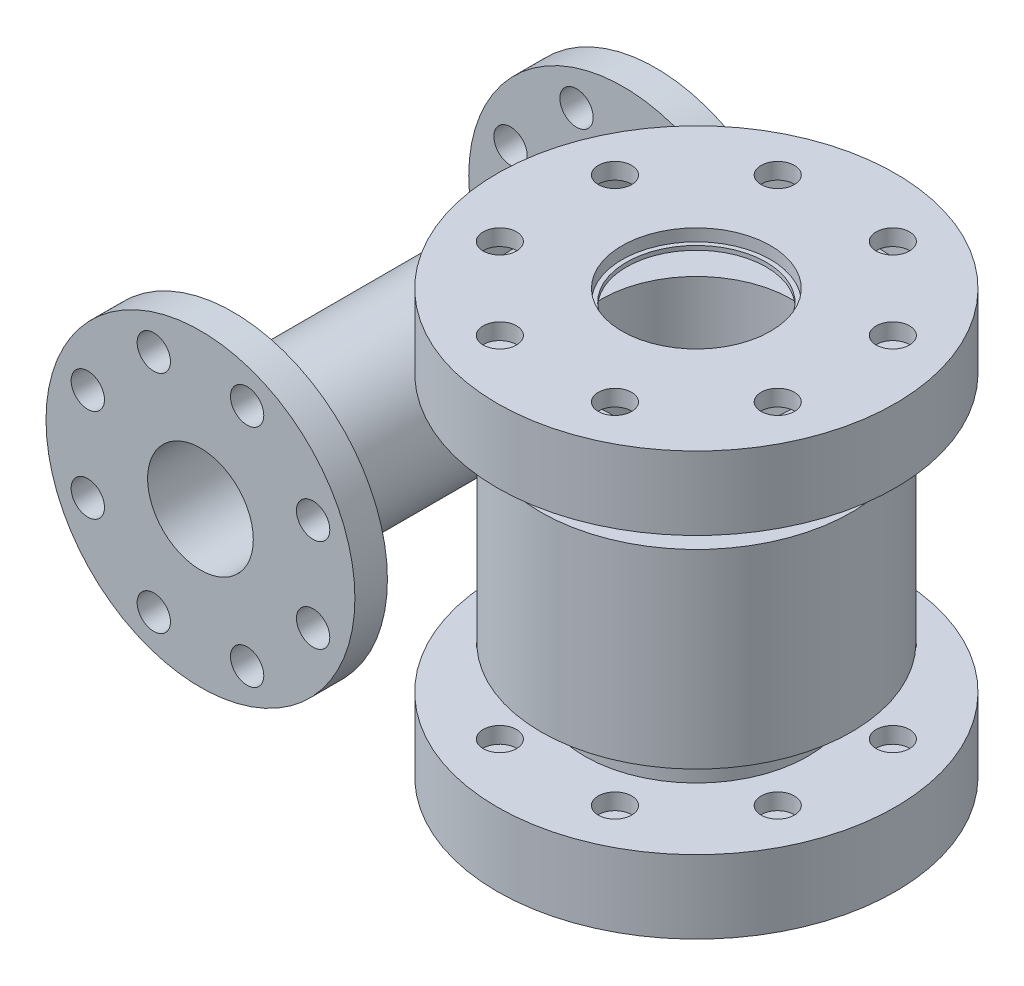
SolidWorks part; units mm, degrees
ref_plane "Front Plane" through (0, 0, 0) normal (0, 0, 1) x (1, 0, 0)
ref_plane "Top Plane" through (0, 0, 0) normal (0, 1, 0) x (1, 0, 0)
ref_plane "Right Plane" through (0, 0, 0) normal (1, 0, 0) x (0, 0, -1)
sketch "Sketch1" plane through (0, 0, 0) normal (0, 0, 1) x (1, 0, 0)
  line L0 (30.2632, 202.5921) -> (112.5, 202.5921)
  line L1 (112.5, 202.5921) -> (112.5, 177.5921)
  line L2 (112.5, 177.5921) -> (58.5526, 177.5921)
  line L3 (58.5526, 177.5921) -> (58.5526, 131.0921)
  line L4 (58.5526, 131.0921) -> (85.5263, 131.0921)
  line L5 (85.5263, 131.0921) -> (85.5263, 34.0921)
  line L6 (85.5263, 34.0921) -> (58.5526, 34.0921)
  line L7 (58.5526, 34.0921) -> (58.5526, -12.4079)
  line L8 (58.5526, -12.4079) -> (112.5, -12.4079)
  line L9 (112.5, -12.4079) -> (112.5, -37.4079)
  line L10 (112.5, -37.4079) -> (37.3712, -37.4079)
  line L11 (0, 217.4342) -> (0, -150.9868) construction
  line L12 (37.3712, -37.4079) -> (0, -37.4079)
  line L13 (30.2632, 202.5921) -> (0, 202.5921)
  point P2 (112.5, -24.9079)
  dimension "D1" = 25
  dimension "D2" = 97
  dimension "D3" = 12.5
  dimension "D4" = 112.5
  dimension "D5" = 46.5
  dimension "D6" = 46.5
revolve "Revolve-Thin1" add sketch "Sketch1" angle 360 about L11 wall 10
sketch "Sketch2" plane through (0, 212.5921, 0) normal (0, 1, 0) x (1, 0, 0)
  line L0 (0, 92.5) -> (0, 0) construction
  line L1 (0, 0) -> (-35.3982, 85.4589) construction
  circle A0 centre (0, 0) radius 92.5 construction
  circle A1 centre (-35.3982, 85.4589) radius 10.25
  circle A2 centre (35.3982, 85.4589) radius 10.25
  circle A3 centre (85.4589, 35.3982) radius 10.25
  circle A4 centre (85.4589, -35.3982) radius 10.25
  circle A5 centre (35.3982, -85.4589) radius 10.25
  circle A6 centre (-35.3982, -85.4589) radius 10.25
  circle A7 centre (-85.4589, -35.3982) radius 10.25
  circle A8 centre (-85.4589, 35.3982) radius 10.25
  point P22 (0, 0)
  dimension "D1" = 185
  dimension "D3" = 20.5
  dimension "D2" = 22.5
  dimension "D4" = 8
extrude "Cut-Extrude2" cut sketch "Sketch2" against normal up to surface (45 mm away) up to face at (0, 167.5921, 122.5)
sketch "Sketch3" plane through (0, -47.4079, 0) normal (0, -1, 0) x (1, 0, 0)
  line L0 (-35.3982, 85.4589) -> (0, 0) construction
  line L1 (0, 0) -> (0, 92.5) construction
  circle A0 centre (0, 0) radius 92.5 construction
  circle A1 centre (-35.3982, 85.4589) radius 10.25
  circle A2 centre (0.0003, 0.0007) radius 92.5 construction
  circle A3 centre (35.3985, 85.4596) radius 10.25
  circle A4 centre (0.001, 0.001) radius 92.5 construction
  circle A5 centre (85.4599, 35.3992) radius 10.25
  circle A6 centre (0.0017, 0.0007) radius 92.5 construction
  circle A7 centre (85.4606, -35.3975) radius 10.25
  circle A8 centre (0.002, 0) radius 92.5 construction
  circle A9 centre (35.4002, -85.4589) radius 10.25
  circle A10 centre (0.0017, -0.0007) radius 92.5 construction
  circle A11 centre (-35.3965, -85.4596) radius 10.25
  circle A12 centre (0.001, -0.001) radius 92.5 construction
  circle A13 centre (-85.4579, -35.3992) radius 10.25
  circle A14 centre (0.0003, -0.0007) radius 92.5 construction
  circle A15 centre (-85.4586, 35.3975) radius 10.25
  point P37 (0.001, 0)
  dimension "D1" = 185
  dimension "D2" = 20.5
  dimension "D3" = 22.5
  dimension "D4" = 8
extrude "Cut-Extrude3" cut sketch "Sketch3" against normal up to surface (45 mm away) up to face at (0, -2.4079, 68.5526)
sketch "Sketch4" plane through (0, 0, 0) normal (0, 0, 1) x (1, 0, 0)
  line L0 (0, -47.4079) -> (0, 212.5921) construction
  line L1 (-122.5, -47.4079) -> (122.5, -47.4079) construction
  line L2 (122.5, 212.5921) -> (-122.5, 212.5921) construction
  line L3 (0, 82.5921) -> (-165, 82.5921) construction
  circle A0 centre (-165, 82.5921) radius 48.5
  dimension "D2" = 97
  dimension "D1" = 165
extrude "Boss-Extrude2" add sketch "Sketch4" along normal mid plane 280 separate body
sketch3d "3DSketch1"
  circle A0 centre (-165, 82.5921, 140) radius 48.5 construction
  circle A1 centre (-165, 82.5921, 140) radius 48.5
  point P2 (-165, 82.5921, 188.5)
  point P4 (-165, 82.5921, 188.5)
  point P5 (0, 0, 0)
sketch "Sketch5" plane through (0, 0, 140) normal (0, 0, 1) x (1, 0, 0)
  circle A0 centre (-165, 82.5921) radius 95
  dimension "D1" = 190
extrude "Boss-Extrude3" add sketch "Sketch5" against normal blind 20
sketch "Sketch6" plane through (0, 0, 140) normal (0, 0, 1) x (1, 0, 0)
  line L0 (-193.7013, 151.8831) -> (-165, 82.5921) construction
  line L1 (-165, 82.5921) -> (-165, 157.5921) construction
  circle A0 centre (-165, 82.5921) radius 75 construction
  circle A1 centre (-193.7013, 151.8831) radius 10.25
  circle A2 centre (-136.2987, 151.8831) radius 10.25
  circle A3 centre (-95.709, 111.2934) radius 10.25
  circle A4 centre (-95.709, 53.8908) radius 10.25
  circle A5 centre (-136.2987, 13.3011) radius 10.25
  circle A6 centre (-193.7013, 13.3011) radius 10.25
  circle A7 centre (-234.291, 53.8908) radius 10.25
  circle A8 centre (-234.291, 111.2934) radius 10.25
  point P22 (-165, 82.5921)
  dimension "D1" = 150
  dimension "D3" = 20.5
  dimension "D2" = 22.5
  dimension "D4" = 8
extrude "Cut-Extrude4" cut sketch "Sketch6" against normal blind 20
mirror "Mirror1" about plane through (0, 0, 0) normal (0, 0, 1) of "Boss-Extrude3"
mirror "Mirror2" about plane through (0, 0, 0) normal (0, 0, 1) of "Cut-Extrude4"
sketch "Sketch7" plane through (0, 0, 140) normal (0, 0, 1) x (1, 0, 0)
  circle A0 centre (-165, 82.5921) radius 32.5
  dimension "D1" = 65
extrude "Cut-Extrude5" cut sketch "Sketch7" against normal through all
sketch "Sketch8" plane through (0, 0, 0) normal (0, 0, 1) x (1, 0, 0)
  line L0 (0, -47.4079) -> (0, 212.5921) construction
  line L1 (-122.5, -47.4079) -> (122.5, -47.4079) construction
  line L2 (122.5, 212.5921) -> (-122.5, 212.5921) construction
  line L3 (45.6482, 212.5921) -> (45.6482, 205.1489)
  line L4 (45.6482, 205.1489) -> (42.9218, 205.1489)
  line L5 (42.9218, 205.1489) -> (42.9218, 198.5242)
  line L6 (42.9218, 198.5242) -> (50, 198.5242)
  line L7 (50, 198.5242) -> (50, 120.3529)
  line L8 (50, 120.3529) -> (59.7691, 120.3529)
  line L9 (59.7691, 120.3529) -> (59.7691, 82.5921)
  line L10 (59.7691, 44.3897) -> (46, 44.3897)
  line L11 (46, 44.3897) -> (46, 29.8154)
  line L12 (46, 29.8154) -> (36.5, 29.8154)
  line L13 (36.5, 29.8154) -> (36.5, 18.3326)
  line L14 (36.5, 18.3326) -> (44, 18.3326)
  line L15 (44, 18.3326) -> (44, -28.0403)
  line L16 (44, -28.0403) -> (36.5, -28.0403)
  line L17 (45.6482, 212.5921) -> (0, 212.5921)
  line L18 (36.5, -28.0403) -> (36.5, -47.4079)
  line L19 (0, 82.5921) -> (178.939, 82.5921) construction
  line L20 (59.7691, 82.5921) -> (59.7691, 44.3897)
  line L21 (0, -47.4079) -> (36.5, -47.4079)
  line L22 (0, -47.4079) -> (0, 212.5921)
  point P9 (46, 37.1025)
  point P23 (36.5, 24.074)
  dimension "D1" = 50
  dimension "D2" = 42.9218
  dimension "D3" = 46
  dimension "D4" = 36.5
revolve "Cut-Revolve2" cut sketch "Sketch8" angle 360 about L22
sketch "Sketch9" plane through (0, 0, 0) normal (1, 0, 0) x (0, 0, -1)
  line L0 (0, -47.4079) -> (0, 212.5921) construction
  line L1 (-122.5, -47.4079) -> (122.5, -47.4079) construction
  line L2 (45.6482, 212.5921) -> (-45.6482, 212.5921) construction
